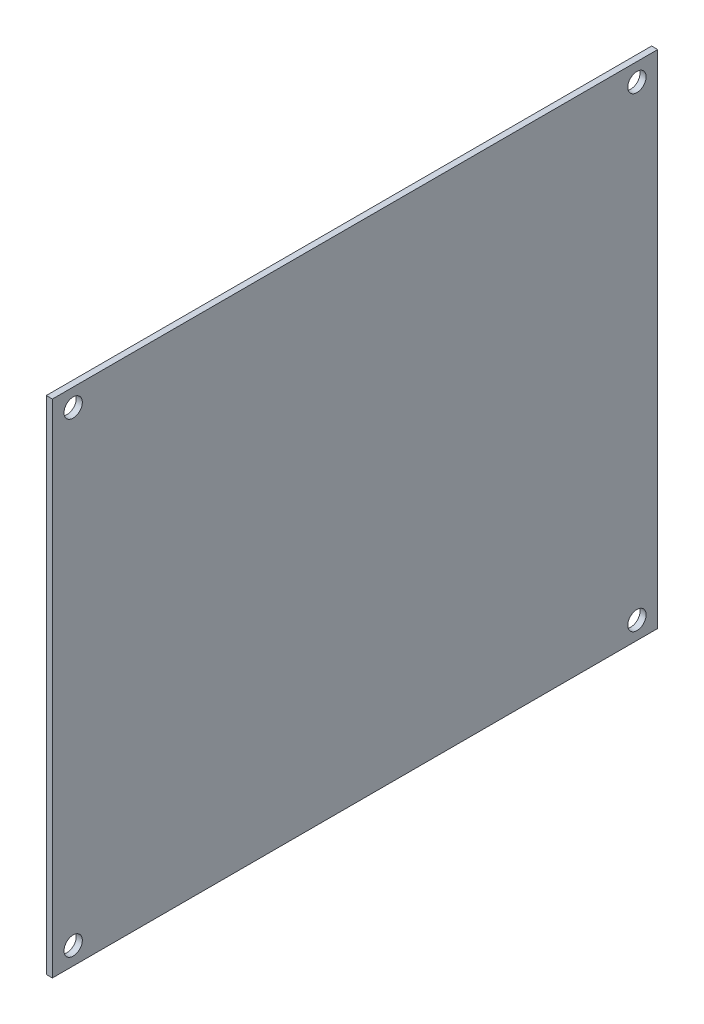
SolidWorks part; units mm, degrees
material "PET"
ref_plane "Front Plane" through (0, 0, 0) normal (1, 0, 0) x (0, 1, 0)
ref_plane "Top Plane" through (0, 0, 0) normal (0, 0, 1) x (0, 1, 0)
ref_plane "Right Plane" through (0, 0, 0) normal (0, 1, 0) x (-1, 0, 0)
sketch "Sketch1" plane through (0, 0, 0) normal (1, 0, 0) x (0, 1, 0)
  line L1 (0, 0) -> (82, 0)
  line L2 (0, 0) -> (0, 99)
  line L3 (0, 99) -> (82, 99)
  line L4 (82, 0) -> (82, 99)
  circle A0 centre (2.9, 3.4) radius 1.5
  circle A1 centre (2.9, 95.6) radius 1.5
  circle A2 centre (79.1, 95.6) radius 1.5
  circle A3 centre (79.1, 3.4) radius 1.5
  dimension "D3" = 3
  dimension "D1" = 99
  dimension "D2" = 82
  dimension "D4" = 3.4
  dimension "D5" = 2.9
  dimension "D6" = 2.9
  dimension "D7" = 3.4
extrude "Boss-Extrude1" add sketch "Sketch1" along normal blind 1
